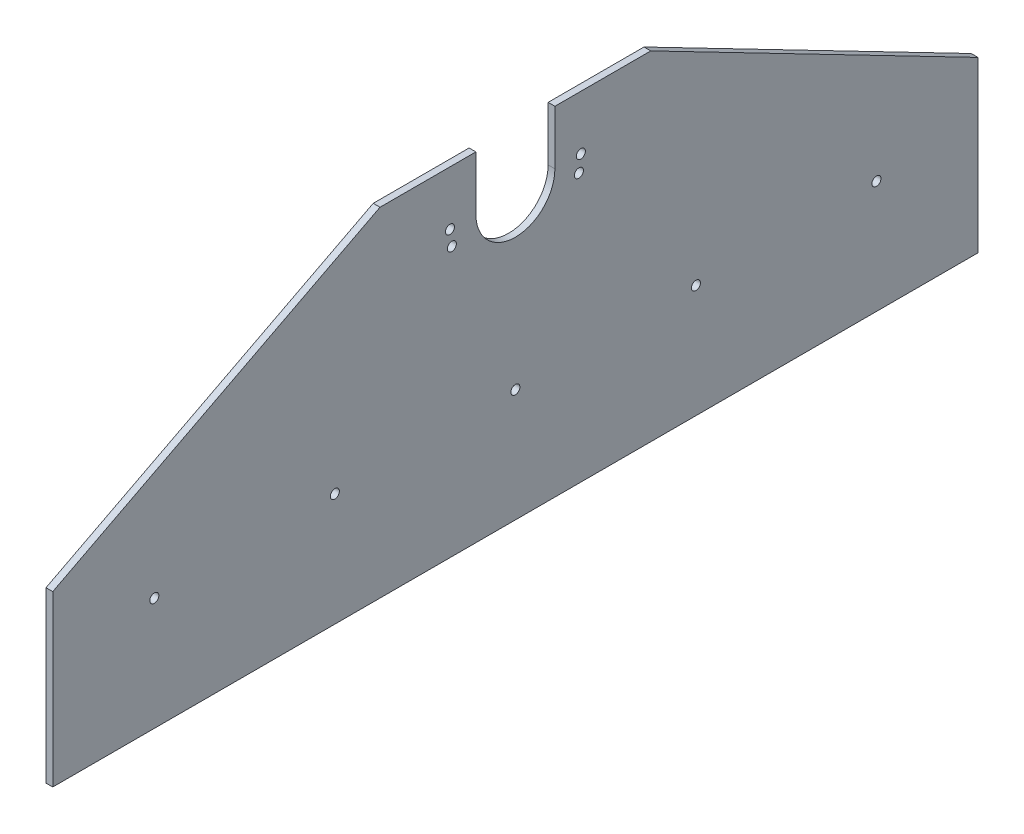
SolidWorks part; units mm, degrees
ref_plane "Ön Düzlem" through (0, 0, 0) normal (0, 0, 1) x (1, 0, 0)
ref_plane "Üst Düzlem" through (0, 0, 0) normal (0, 1, 0) x (1, 0, 0)
ref_plane "Sağ Düzlem" through (0, 0, 0) normal (1, 0, 0) x (0, 0, -1)
sketch "Sketch1" plane through (0, 0, 0) normal (1, 0, 0) x (0, 0, -1)
  line L1 (0, 0) -> (410, 0)
  line L2 (0, 0) -> (0, 150)
  line L3 (0, 150) -> (410, 150)
  line L4 (410, 0) -> (410, 150)
  dimension "D1" = 410
  dimension "D2" = 150
extrude "Boss-Extrude1" add sketch "Sketch1" along normal blind 3
sketch "Sketch2" plane through (3, 0, 0) normal (1, 0, 0) x (0, 0, -1)
  line L0 (205, 150) -> (205, 0) construction
  line L1 (410, 150) -> (0, 150) construction
  line L2 (0, 0) -> (410, 0) construction
  line L3 (145, 150) -> (0, 75)
  line L4 (0, 150) -> (0, 0) construction
  line L5 (0, 75) -> (0, 150)
  line L6 (0, 150) -> (145, 150)
  line L7 (265, 150) -> (410, 75)
  line L8 (410, 75) -> (410, 150)
  line L9 (410, 150) -> (265, 150)
  dimension "D1" = 60
  dimension "D2" = 75
extrude "Cut-Extrude1" cut sketch "Sketch2" against normal blind 3
sketch "Sketch3" plane through (3, 0, 0) normal (1, 0, 0) x (0, 0, -1)
  line L0 (0, 50) -> (410, 50) construction
  line L1 (0, 75) -> (0, 0) construction
  line L2 (410, 0) -> (410, 75) construction
  line L3 (0, 0) -> (410, 0) construction
  circle A0 centre (45, 50) radius 2
  circle A1 centre (125, 50) radius 2
  circle A2 centre (205, 50) radius 2
  circle A3 centre (285, 50) radius 2
  circle A4 centre (365, 50) radius 2
  dimension "D3" = 4
  dimension "D1" = 50
  dimension "D2" = 45
  dimension "D5" = 80
  dimension "D4" = 5
extrude "Cut-Extrude2" cut sketch "Sketch3" against normal blind 3
sketch "Sketch4" plane through (3, 0, 0) normal (1, 0, 0) x (0, 0, -1)
  line L0 (205, 0) -> (205, 160.4233) construction
  line L1 (0, 0) -> (410, 0) construction
  line L2 (265, 150) -> (145, 150) construction
  line L3 (205, 126) -> (176, 126) construction
  line L4 (205, 126) -> (176.845, 119.0512) construction
  line L5 (176, 126) -> (176.845, 119.0512) construction
  circle A0 centre (205, 126) radius 25 construction
  circle A1 centre (176, 126) radius 2
  circle A2 centre (176.845, 119.0512) radius 2
  circle A3 centre (205, 126) radius 17.5
  circle A4 centre (233.155, 119.0512) radius 2
  circle A5 centre (234, 126) radius 2
  dimension "D1" = 50
  dimension "D5" = 4
  dimension "D7" = 35
  dimension "D2" = 24
  dimension "D3" = 29
  dimension "D4" = 7
  dimension "D6" = 28.155
extrude "Cut-Extrude3" cut sketch "Sketch4" against normal blind 10
sketch "Sketch5" plane through (3, 0, 0) normal (1, 0, 0) x (0, 0, -1)
  line L0 (187.5, 126) -> (187.5, 150)
  line L1 (265, 150) -> (145, 150) construction
  line L2 (187.5, 150) -> (222.5, 150)
  line L3 (222.5, 150) -> (222.5, 126)
  line L4 (222.5, 126) -> (187.5, 126)
  circle A0 centre (205, 126) radius 17.5 construction
  dimension "D1" = 35
extrude "Cut-Extrude4" cut sketch "Sketch5" against normal blind 10
